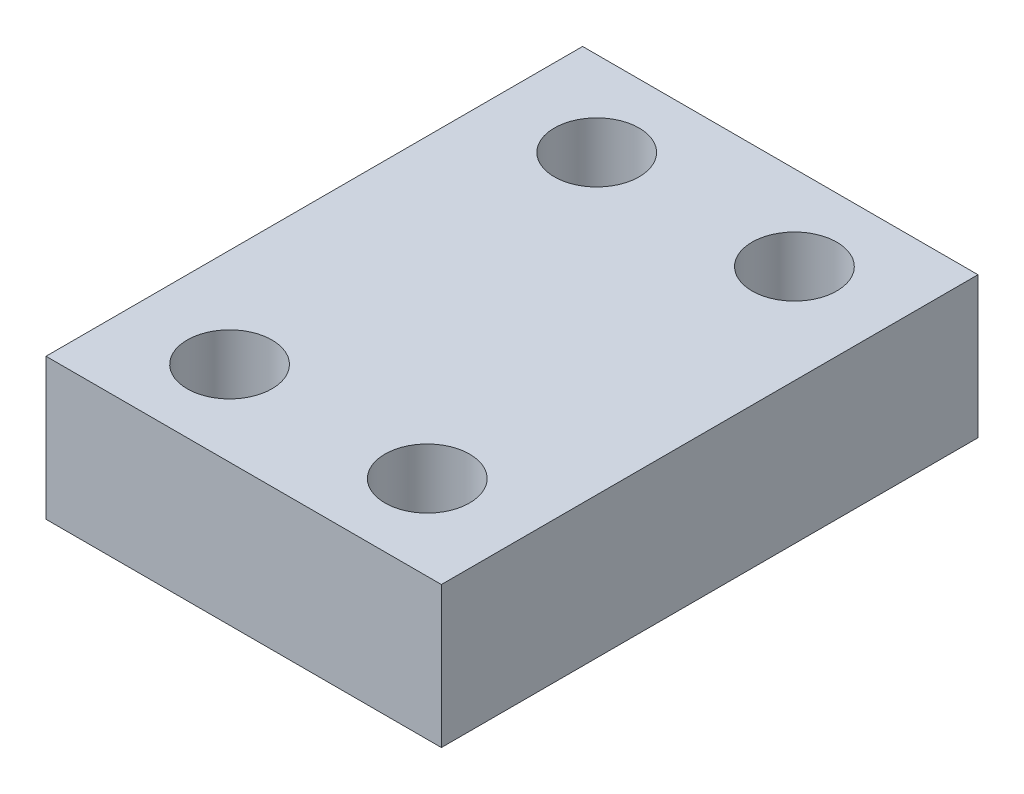
SolidWorks part; units mm, degrees
ref_plane "前视基准面" through (0, 0, 0) normal (0, 0, 1) x (1, 0, 0)
ref_plane "上视基准面" through (0, 0, 0) normal (0, 1, 0) x (1, 0, 0)
ref_plane "右视基准面" through (0, 0, 0) normal (1, 0, 0) x (0, 0, -1)
sketch "草图1" plane through (0, 0, 0) normal (0, 1, 0) x (1, 0, 0)
  line L0 (0, 9.5) -> (0, 0) construction
  line L1 (-7, 9.5) -> (7, 9.5)
  line L2 (-7, 9.5) -> (-7, -9.5)
  line L3 (-7, -9.5) -> (7, -9.5)
  line L4 (7, 9.5) -> (7, -9.5)
  line L5 (-7, 9.5) -> (7, -9.5) construction
  line L6 (-7, -9.5) -> (7, 9.5) construction
  line L7 (0, 0) -> (7, 0) construction
  circle A0 centre (3.5, 6.5) radius 1.5
  circle A1 centre (-3.5, 6.5) radius 1.5
  circle A2 centre (-3.5, -6.5) radius 1.5
  circle A3 centre (3.5, -6.5) radius 1.5
  point P0 (0, 0)
  dimension "D3" = 3
  dimension "D4" = 7
  dimension "D5" = 13
  dimension "D1" = 19
  dimension "D2" = 14
extrude "凸台-拉伸1" add sketch "草图1" along normal blind 5
